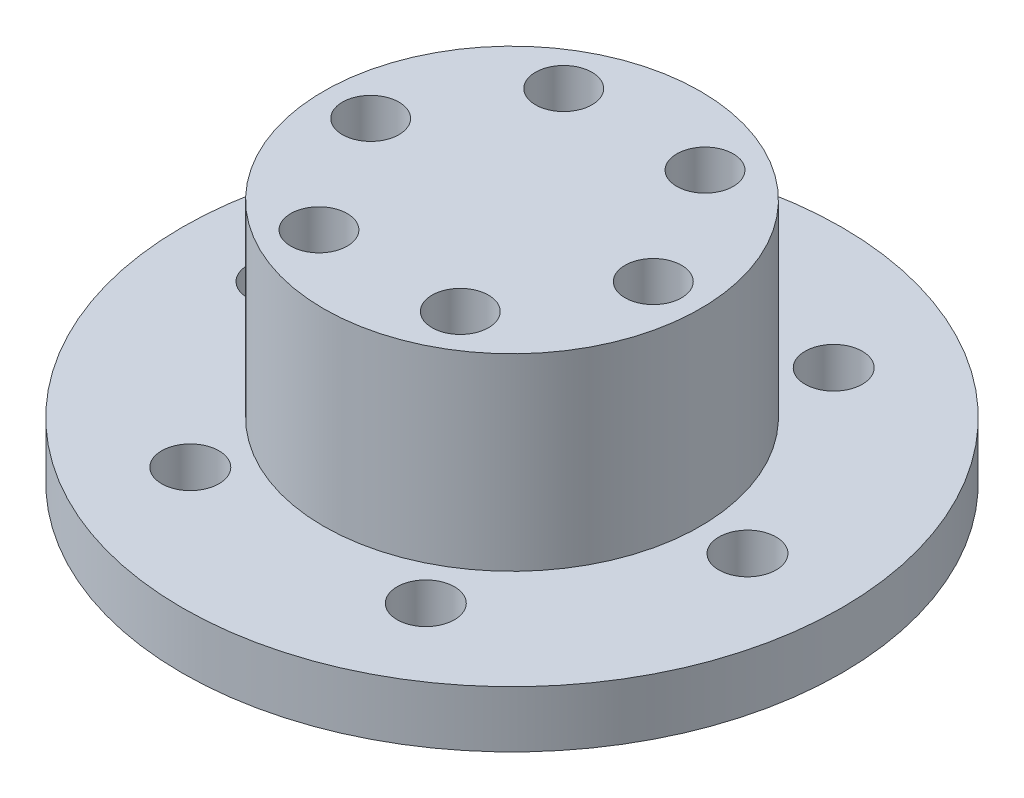
SolidWorks part; units mm, degrees
ref_plane "Alzado" through (0, 0, 0) normal (0, 0, 1) x (1, 0, 0)
ref_plane "Planta" through (0, 0, 0) normal (0, 1, 0) x (1, 0, 0)
ref_plane "Vista lateral" through (0, 0, 0) normal (1, 0, 0) x (0, 0, -1)
sketch "Croquis1" plane through (0, 0, 0) normal (0, 1, 0) x (1, 0, 0)
  circle A0 centre (0, 0) radius 12.5 construction
  circle A1 centre (12.5, 0) radius 1.52
  circle A2 centre (6.25, -10.8253) radius 1.52
  circle A3 centre (-6.25, -10.8253) radius 1.52
  circle A4 centre (-12.5, 0) radius 1.52
  circle A5 centre (-6.25, 10.8253) radius 1.52
  circle A6 centre (6.25, 10.8253) radius 1.52
  circle A7 centre (0, 0) radius 17.5
  point P17 (0, 0)
  dimension "D1" = 25
  dimension "D2" = 3.04
  dimension "D4" = 35
  dimension "D3" = 6
extrude "Saliente-Extruir1" add sketch "Croquis1" along normal blind 3
sketch "Croquis2" plane through (0, 3, 0) normal (0, 1, 0) x (1, 0, 0)
  circle A0 centre (0, 0) radius 10
  circle A1 centre (0, 0) radius 7.5 construction
  circle A2 centre (7.5, 0) radius 1.5
  circle A3 centre (3.75, -6.4952) radius 1.5
  circle A4 centre (-3.75, -6.4952) radius 1.5
  circle A5 centre (-7.5, 0) radius 1.5
  circle A6 centre (-3.75, 6.4952) radius 1.5
  circle A7 centre (3.75, 6.4952) radius 1.5
  point P18 (0, 0)
  dimension "D1" = 20
  dimension "D2" = 15
  dimension "D3" = 3
  dimension "D4" = 6
extrude "Saliente-Extruir2" add sketch "Croquis2" along normal blind 10
